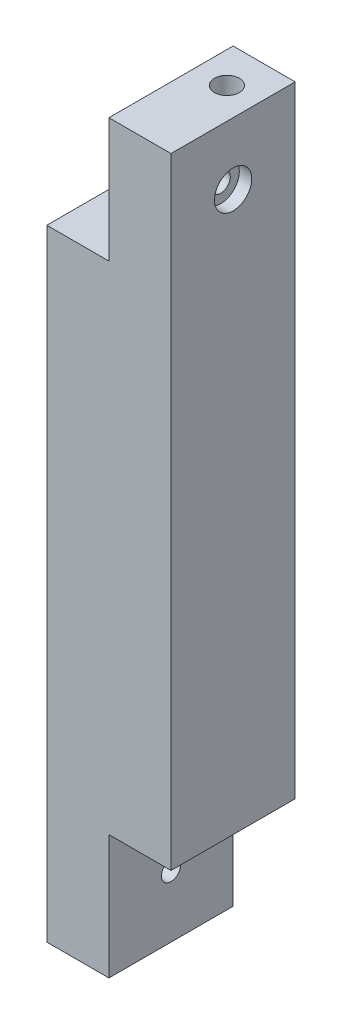
SolidWorks part; units mm, degrees
ref_plane "前视基准面" through (0, 0, 0) normal (0, 0, 1) x (1, 0, 0)
ref_plane "上视基准面" through (0, 0, 0) normal (0, 1, 0) x (1, 0, 0)
ref_plane "右视基准面" through (0, 0, 0) normal (1, 0, 0) x (0, 0, -1)
other "Configuration Table"
sketch "草图1" plane through (0, 0, 0) normal (0, 1, 0) x (1, 0, 0)
  line L1 (-17.9813, 3.5461) -> (2.0187, 3.5461)
  line L2 (-17.9813, 3.5461) -> (-17.9813, -16.4539)
  line L3 (-17.9813, -16.4539) -> (2.0187, -16.4539)
  line L4 (2.0187, 3.5461) -> (2.0187, -16.4539)
extrude "凸台-拉伸1" add sketch "草图1" along normal blind 120 contours L2 L1 L4 L3
sketch "草图2" plane through (0, 0, 16.4539) normal (0, 0, 1) x (1, 0, 0)
  line L1 (-17.9813, 120) -> (-7.9813, 120)
  line L2 (-17.9813, 120) -> (-17.9813, 100)
  line L3 (-17.9813, 100) -> (-7.9813, 100)
  line L4 (-7.9813, 120) -> (-7.9813, 100)
extrude "切除-拉伸1" cut sketch "草图2" against normal blind 120 contours L2 L1 L4 L3
sketch "草图3" plane through (0, 0, 16.4539) normal (0, 0, 1) x (1, 0, 0)
  line L1 (2.0187, 0) -> (-7.9813, 0)
  line L2 (2.0187, 0) -> (2.0187, 20)
  line L3 (2.0187, 20) -> (-7.9813, 20)
  line L4 (-7.9813, 0) -> (-7.9813, 20)
extrude "切除-拉伸2" cut sketch "草图3" against normal blind 120 contours L2 L1 L4 L3
sketch "草图4" plane through (-7.9813, 0, 0) normal (-1, 0, 0) x (0, 0, 1)
  line L0 (-3.5461, 120) -> (16.4539, 100)
  circle A0 centre (6.4539, 110) radius 1.55
extrude "切除-拉伸3" cut sketch "草图4" against normal blind 120 contours L0 A0 | L0 A0
sketch "草图5" plane through (2.0187, 0, 0) normal (1, 0, 0) x (0, 0, -1)
  circle A0 centre (-6.4539, 110) radius 3
extrude "切除-拉伸4" cut sketch "草图5" against normal blind 2
sketch "草图6" plane through (-7.9813, 0, 0) normal (1, 0, 0) x (0, 0, -1)
  line L0 (-16.4539, 20) -> (3.5461, 0)
  circle A0 centre (-6.4539, 10) radius 1.55
extrude "切除-拉伸5" cut sketch "草图6" against normal blind 20 contours L0 A0 | L0 A0
sketch "草图7" plane through (-17.9813, 0, 0) normal (-1, 0, 0) x (0, 0, 1)
  circle A0 centre (6.4539, 10) radius 3
extrude "切除-拉伸6" cut sketch "草图7" against normal blind 2
sketch "草图8" plane through (0, 20, 0) normal (0, -1, 0) x (1, 0, 0)
  line L0 (-7.9813, 16.4539) -> (2.0187, -3.5461)
  line L1 (-2.9813, 6.4539) -> (-2.9813, 2.4539)
  circle A0 centre (-2.9813, 2.4539) radius 2
extrude "切除-拉伸7" cut sketch "草图8" against normal blind 100
